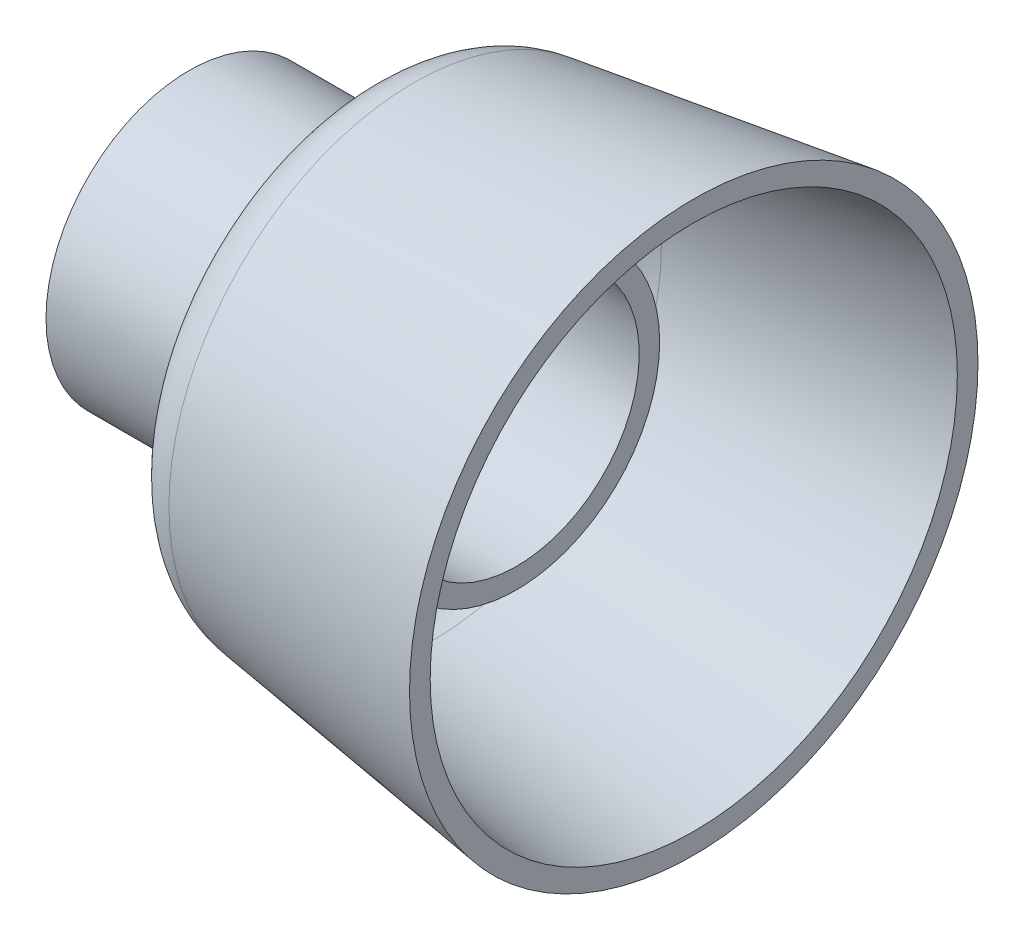
SolidWorks part; units mm, degrees
ref_plane "Front Plane" through (0, 0, 0) normal (0, 0, 1) x (1, 0, 0)
ref_plane "Top Plane" through (0, 0, 0) normal (0, 1, 0) x (1, 0, 0)
ref_plane "Right Plane" through (0, 0, 0) normal (1, 0, 0) x (0, 0, -1)
sketch "Sketch1" plane through (0, 0, 0) normal (0, 0, 1) x (1, 0, 0)
  line L0 (0, 0) -> (59.6872, 0) construction
  line L1 (0, 11.1125) -> (12.7, 11.1125)
  line L2 (12.7, 11.1125) -> (14.007, 18.525)
  line L3 (14.007, 18.525) -> (39.1598, 22.06)
  line L4 (0, 11.1125) -> (0, 9.525)
  line L5 (0, 9.525) -> (25.4, 9.525)
  line L6 (15.5945, 17.145) -> (14.5308, 11.1125)
  line L7 (15.5945, 17.145) -> (39.1598, 20.4569)
  line L8 (39.1598, 22.06) -> (39.1598, 20.4569)
  line L9 (0, 9.525) -> (0, 0) construction
  line L10 (14.5308, 11.1125) -> (25.4, 11.1125)
  line L11 (25.4, 11.1125) -> (25.4, 9.525)
  dimension "D1" = 9.525
  dimension "D2" = 12.7
  dimension "D3" = 100
  dimension "D4" = 108
  dimension "D5" = 1.5875
  dimension "D6" = 1.5875
  dimension "D7" = 12.7
  dimension "D8" = 7.62
  dimension "D9" = 25.4
  dimension "D10" = 1.5875
  dimension "D11" = 1.5875
revolve "Revolve1" add sketch "Sketch1" angle 360 about L0
fillet "Fillet1" radius 4.7625 2 edges at (14.007, 0, 18.525) (15.5945, 0, 17.145)
